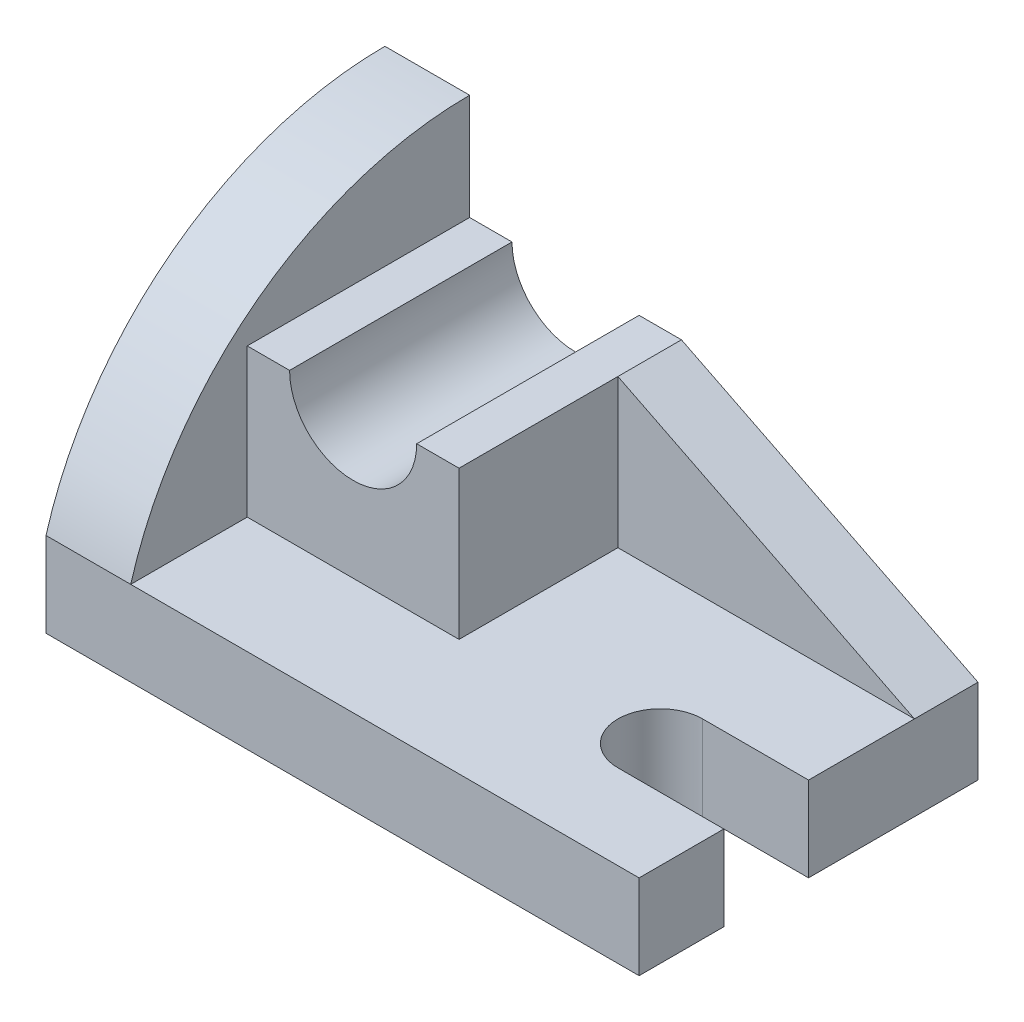
SolidWorks part; units mm, degrees
ref_plane "Front Plane" through (0, 0, 0) normal (0, 0, 1) x (1, 0, 0)
ref_plane "Top Plane" through (0, 0, 0) normal (0, 1, 0) x (1, 0, 0)
ref_plane "Right Plane" through (0, 0, 0) normal (1, 0, 0) x (0, 0, -1)
sketch "Sketch1" plane through (0, 0, 0) normal (0, 1, 0) x (1, 0, 0)
  line L1 (-48, 32) -> (48, 32)
  line L2 (-48, 32) -> (-48, -32)
  line L3 (-48, -32) -> (48, -32)
  line L4 (48, 32) -> (48, -32)
  line L5 (-48, 32) -> (48, -32) construction
  line L6 (-48, -32) -> (48, 32) construction
  point P0 (0, 0)
  dimension "D1" = 96
  dimension "D2" = 64
extrude "Boss-Extrude1" add sketch "Sketch1" along normal blind 16
sketch "Sketch2" plane through (0, 16, 0) normal (0, 1, 0) x (1, 0, 0)
  line L0 (48, -16) -> (28, -16)
  line L1 (48, -32) -> (48, 32) construction
  line L2 (48, 0) -> (28, 0)
  line L3 (-48, -32) -> (48, -32) construction
  arc A0 (28, -16) -> (28, 0) centre (28, -8) cw
  point P9 (0, 0)
  dimension "D1" = 20
  dimension "D2" = 20
  dimension "D3" = 16
  dimension "D4" = 16
extrude "Cut-Extrude1" cut sketch "Sketch2" against normal blind 16 and the other way through all
sketch "Sketch3" plane through (0, 0, -32) normal (0, 0, -1) x (-1, 0, 0)
  line L0 (-48, 16) -> (8, 44)
  line L1 (8, 44) -> (8, 16)
  line L2 (-48, 16) -> (48, 16) construction
  line L3 (-48, 16) -> (-48, 0) construction
  line L4 (-48, 16) -> (8, 16)
  dimension "D1" = 28
  dimension "D2" = 56
extrude "Boss-Extrude3" add sketch "Sketch3" against normal blind 12
sketch "Sketch4" plane through (0, 0, -32) normal (0, 0, -1) x (-1, 0, 0)
  line L0 (8, 44) -> (16, 44)
  line L1 (8, 16) -> (8, 44) construction
  line L2 (48, 16) -> (48, 44)
  line L3 (48, 44) -> (40, 44)
  line L4 (48, 16) -> (48, 0) construction
  line L5 (8, 44) -> (8, 16)
  line L6 (8, 16) -> (48, 16)
  arc A0 (16, 44) -> (40, 44) centre (28, 44) ccw
  dimension "D1" = 8
  dimension "D2" = 8
extrude "Boss-Extrude4" add sketch "Sketch4" against normal blind 42
sketch "Sketch6" plane through (-48, 0, 0) normal (-1, 0, 0) x (0, 0, 1)
  line L0 (-32, 0) -> (-32, 64)
  line L1 (32, 16) -> (32, 0) construction
  line L2 (32, 16) -> (32, 0)
  line L3 (32, 0) -> (-32, 0)
  arc A0 (-32, 64) -> (32, 16) centre (-32, -2.6667) cw
  dimension "D1" = 64
extrude "Boss-Extrude6" add sketch "Sketch6" along normal blind 16
